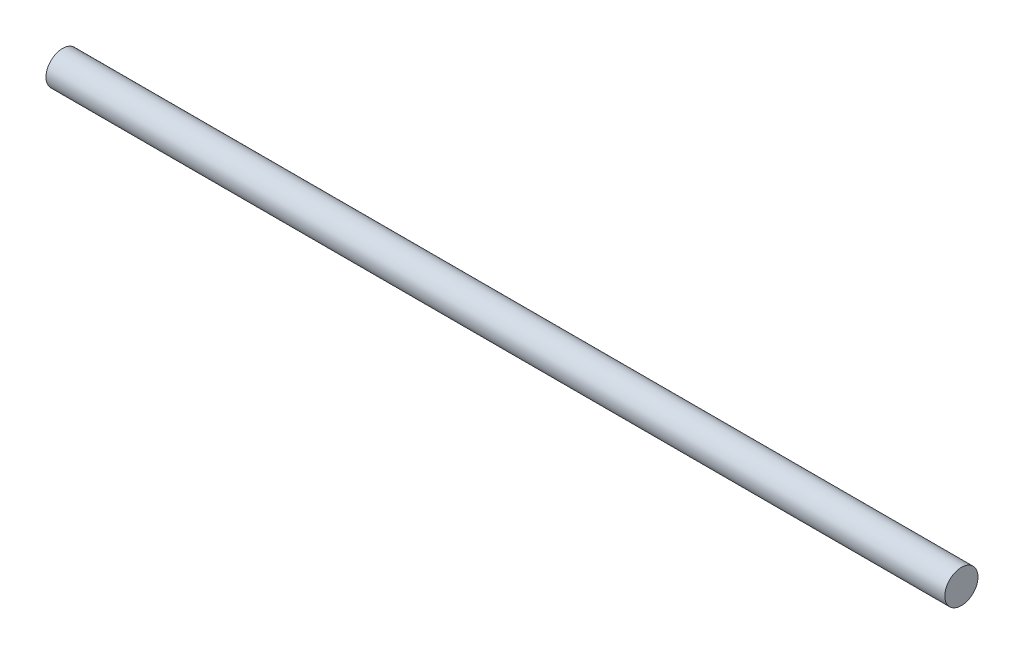
SolidWorks part; units mm, degrees
ref_plane "Front Plane" through (0, 0, 0) normal (0, 0, 1) x (1, 0, 0)
ref_plane "Top Plane" through (0, 0, 0) normal (0, 1, 0) x (1, 0, 0)
ref_plane "Right Plane" through (0, 0, 0) normal (1, 0, 0) x (0, 0, -1)
sketch "Sketch1" plane through (0, 0, 0) normal (1, 0, 0) x (0, 0, -1)
  circle A0 centre (0, 0) radius 10.3187
  dimension "D1" = 20.6375
extrude "Tree" add sketch "Sketch1" along normal blind 558.8
